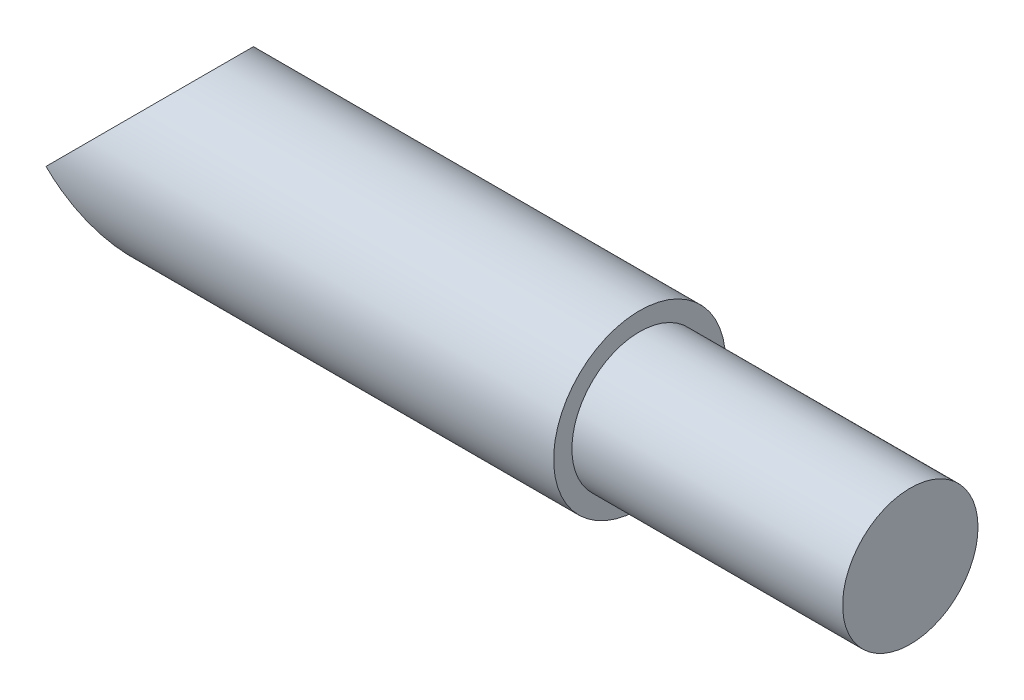
SolidWorks part; units mm, degrees
ref_plane "Front Plane" through (0, 0, 0) normal (0, 0, 1) x (1, 0, 0)
ref_plane "Top Plane" through (0, 0, 0) normal (0, 1, 0) x (1, 0, 0)
ref_plane "Right Plane" through (0, 0, 0) normal (1, 0, 0) x (0, 0, -1)
sketch "Sketch1" plane through (0, 0, 0) normal (1, 0, 0) x (0, 0, -1)
  circle A0 centre (0, 0) radius 12.7
  dimension "D1" = 25.4
extrude "Boss-Extrude1" add sketch "Sketch1" along normal blind 75
sketch "Sketch2" plane through (75, 0, 0) normal (1, 0, 0) x (0, 0, -1)
  circle A0 centre (0, 0) radius 10
  dimension "D1" = 20
sketch "Sketch5" plane through (0, 0, 0) normal (0, 1, 0) x (1, 0, 0)
  circle A0 centre (0, 0) radius 12.7
  dimension "D1" = 25.4
extrude "Cut-Extrude1" cut sketch "Sketch5" against normal mid plane 75
extrude "Boss-Extrude2" add sketch "Sketch2" along normal blind 40
